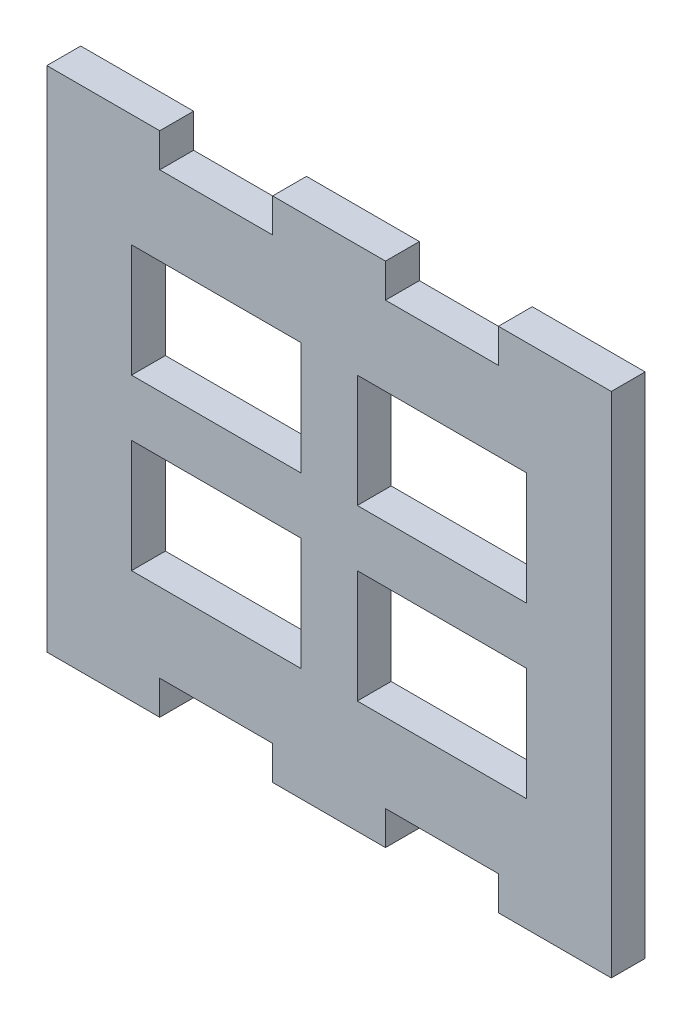
SolidWorks part; units mm, degrees
ref_plane "Plan de face" through (0, 0, 0) normal (0, 0, 1) x (1, 0, 0)
ref_plane "Plan de dessus" through (0, 0, 0) normal (0, 1, 0) x (1, 0, 0)
ref_plane "Plan de droite" through (0, 0, 0) normal (1, 0, 0) x (0, 0, -1)
sketch "Esquisse1" plane through (0, 0, 0) normal (0, 0, 1) x (1, 0, 0)
  line L1 (0, 0) -> (50, 0)
  line L2 (0, 0) -> (0, 45)
  line L3 (0, 45) -> (50, 45)
  line L4 (50, 0) -> (50, 45)
  dimension "D1" = 45
  dimension "D2" = 50
extrude "Boss.-Extru.1" add sketch "Esquisse1" along normal blind 3
sketch "Esquisse2" plane through (0, 0, 3) normal (0, 0, 1) x (1, 0, 0)
  line L1 (0, 0) -> (50, 0) construction
  line L2 (10, 3) -> (20, 3)
  line L3 (10, 3) -> (10, 0)
  line L4 (10, 0) -> (20, 0)
  line L6 (20, 3) -> (20, 0)
  line L7 (0, 45) -> (0, 0) construction
  line L8 (30, 3) -> (40, 3)
  line L9 (30, 3) -> (30, 0)
  line L10 (30, 0) -> (40, 0)
  line L11 (40, 3) -> (40, 0)
  dimension "D1" = 10
  dimension "D2" = 3
  dimension "D3" = 0
  dimension "D4" = 10
  dimension "D5" = 2
extrude "Enlèv. mat.-Extru.1" cut sketch "Esquisse2" against normal blind 10
sketch "Esquisse3" plane through (0, 0, 3) normal (0, 0, 1) x (1, 0, 0)
  line L0 (27.5, 35) -> (42.5, 35)
  line L1 (7.5, 35) -> (22.5, 35)
  line L2 (7.5, 35) -> (7.5, 25)
  line L3 (7.5, 25) -> (22.5, 25)
  line L4 (22.5, 35) -> (22.5, 25)
  line L5 (27.5, 35) -> (27.5, 25)
  line L6 (27.5, 25) -> (42.5, 25)
  line L7 (42.5, 35) -> (42.5, 25)
  line L8 (27.5, 20) -> (42.5, 20)
  line L9 (27.5, 20) -> (27.5, 10)
  line L10 (27.5, 10) -> (42.5, 10)
  line L11 (42.5, 20) -> (42.5, 10)
  line L12 (7.5, 20) -> (22.5, 20)
  line L13 (7.5, 20) -> (7.5, 10)
  line L14 (7.5, 10) -> (22.5, 10)
  line L15 (22.5, 20) -> (22.5, 10)
  line L16 (0, 45) -> (0, 0) construction
  line L17 (50, 45) -> (0, 45) construction
  dimension "D1" = 15
  dimension "D2" = 10
  dimension "D5" = 7.5
  dimension "D6" = 10
  dimension "D3" = 2
  dimension "D4" = 2
extrude "Enlèv. mat.-Extru.2" cut sketch "Esquisse3" against normal blind 10
sketch "Esquisse4" plane through (0, 0, 3) normal (0, 0, 1) x (1, 0, 0)
  line L0 (50, 45) -> (0, 45) construction
  line L1 (10, 45) -> (20, 45)
  line L2 (10, 45) -> (10, 42)
  line L3 (10, 42) -> (20, 42)
  line L4 (20, 45) -> (20, 42)
  line L5 (0, 45) -> (0, 0) construction
  line L6 (30, 45) -> (40, 45)
  line L7 (30, 45) -> (30, 42)
  line L8 (30, 42) -> (40, 42)
  line L9 (40, 45) -> (40, 42)
  dimension "D1" = 10
  dimension "D2" = 10
  dimension "D3" = 3
  dimension "D4" = 2
extrude "Enlèv. mat.-Extru.3" cut sketch "Esquisse4" against normal blind 10
